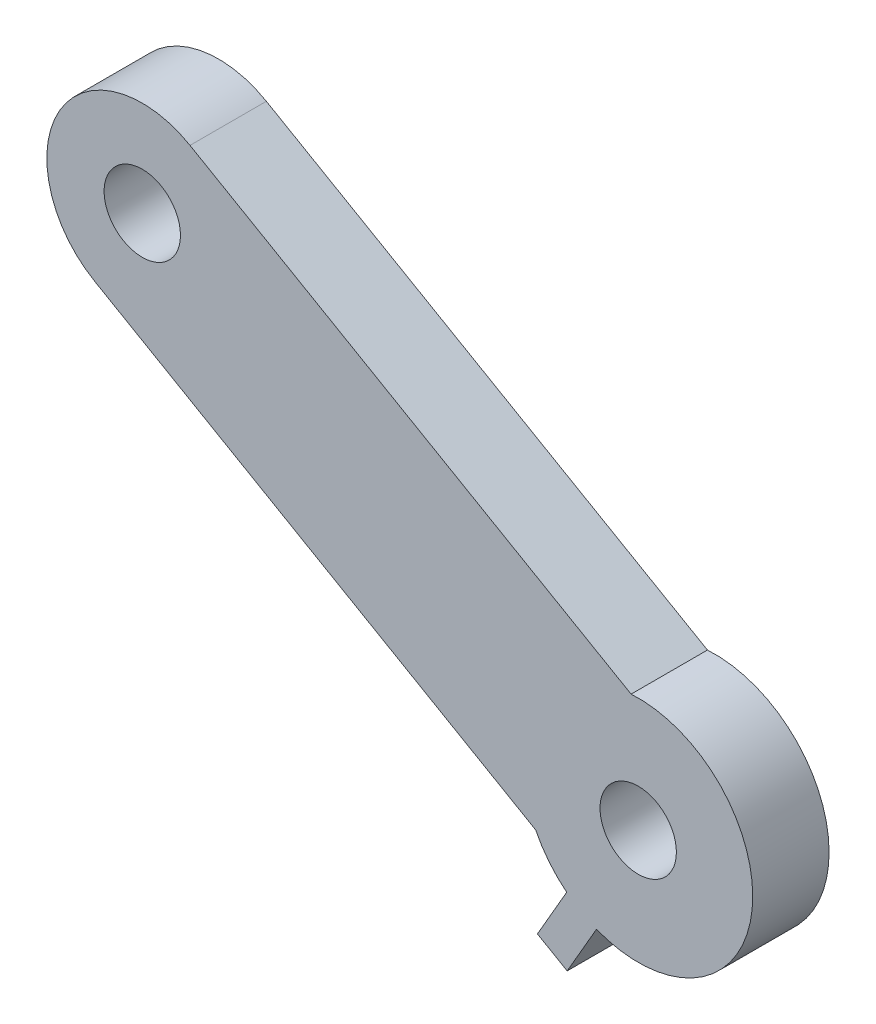
SolidWorks part; units mm, degrees
material "AISI 1020"
ref_plane "Plan de face" through (0, 0, 0) normal (0, 0, 1) x (1, 0, 0)
ref_plane "Plan de dessus" through (0, 0, 0) normal (0, 1, 0) x (1, 0, 0)
ref_plane "Plan de droite" through (0, 0, 0) normal (1, 0, 0) x (0, 0, -1)
sketch "Esquisse1" plane through (0, 0, 0) normal (0, 0, 1) x (1, 0, 0)
  line L0 (-142.4038, 53.3494) -> (-26.8614, -13.3591)
  line L1 (-117.4038, 96.6506) -> (-1.8614, 29.9422)
  line L2 (0, 0) -> (0, 146.0576) construction
  line L8 (0, 0) -> (-45.3156, -78.4889) construction
  line L10 (-16.8971, -20.2667) -> (-9.1029, -24.7667)
  line L11 (-16.8971, -20.2667) -> (-26.3971, -36.7211)
  line L12 (-26.3971, -36.7211) -> (-18.6029, -41.2211)
  line L13 (-9.1029, -24.7667) -> (-18.6029, -41.2211)
  circle A0 centre (0, 0) radius 30
  circle A1 centre (-129.9038, 75) radius 25
  circle A2 centre (0, 0) radius 10
  circle A3 centre (-129.9038, 75) radius 10
  point P23 (-22.5, -38.9711)
  dimension "D1" = 60
  dimension "D2" = 50
  dimension "D5" = 150
  dimension "D6" = 20
  dimension "D7" = 20
  dimension "D3" = 50
  dimension "D4" = 60
  dimension "D11" = 90
  dimension "D12" = 19
  dimension "D13" = 9
  dimension "D14" = 26
extrude "Boss.-Extru.1" add sketch "Esquisse1" along normal blind 20
